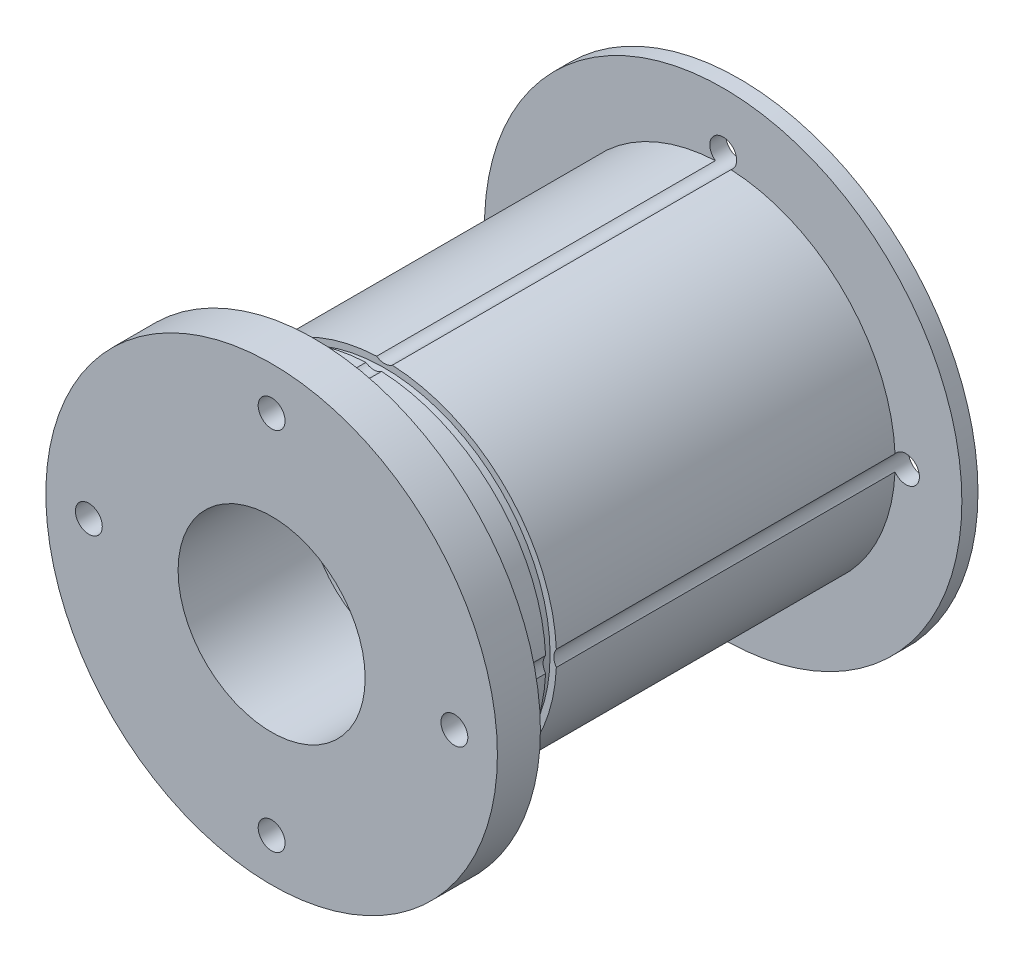
SolidWorks part; units mm, degrees
ref_plane "Спереди" through (0, 0, 0) normal (0, 0, 1) x (1, 0, 0)
ref_plane "Сверху" through (0, 0, 0) normal (0, 1, 0) x (1, 0, 0)
ref_plane "Справа" through (0, 0, 0) normal (1, 0, 0) x (0, 0, -1)
sketch "Эскиз1" plane through (0, 0, 0) normal (0, 0, 1) x (1, 0, 0)
  circle A0 centre (0, 0) radius 16
  circle A1 centre (0, 0) radius 8.7
extrude "Hollow_hub" add sketch "Эскиз1" along normal blind 38 from offset 15
sketch "Эскиз2" plane through (0, 0, 0) normal (0, 0, 1) x (1, 0, 0)
  circle A0 centre (0, 0) radius 22.2
  circle A1 centre (0, 0) radius 13
extrude "Rear_stack_flange" add sketch "Эскиз2" along normal blind 1.5 from offset 16.5
sketch "Эскиз3" plane through (0, 0, 0) normal (0, 0, 1) x (1, 0, 0)
  circle A0 centre (0, 0) radius 21
  circle A1 centre (0, 0) radius 8.7
extrude "Sun_mount_flange" add sketch "Эскиз3" along normal blind 4 from offset 23
sketch "Эскиз4" plane through (0, 0, 0) normal (0, 0, 1) x (1, 0, 0)
  circle A0 centre (0, 0) radius 13
extrude "Rear_rotor_bearing_seat" cut sketch "Эскиз4" along normal blind 5 from offset 15
sketch "Эскиз5" plane through (0, 0, 0) normal (0, 0, 1) x (1, 0, 0)
  circle A0 centre (0, 0) radius 13
extrude "Front_rotor_bearing_seat" cut sketch "Эскиз5" along normal blind 5 from offset 10
sketch "Эскиз6" plane through (0, 0, 0) normal (0, 0, 1) x (1, 0, 0)
  circle A0 centre (0, 0) radius 17
  circle A1 centre (0, 0) radius 15.4
extrude "Circlip_groove" cut sketch "Эскиз6" along normal blind 1 from offset 16.5
sketch "Эскиз7" plane through (0, 0, 0) normal (0, 0, 1) x (1, 0, 0)
  circle A0 centre (17, 0) radius 1.25
  circle A1 centre (0, 17) radius 1.25
  circle A2 centre (-17, 0) radius 1.25
  circle A3 centre (0, -17) radius 1.25
extrude "Through_holes" cut sketch "Эскиз7" against normal mid plane 200
